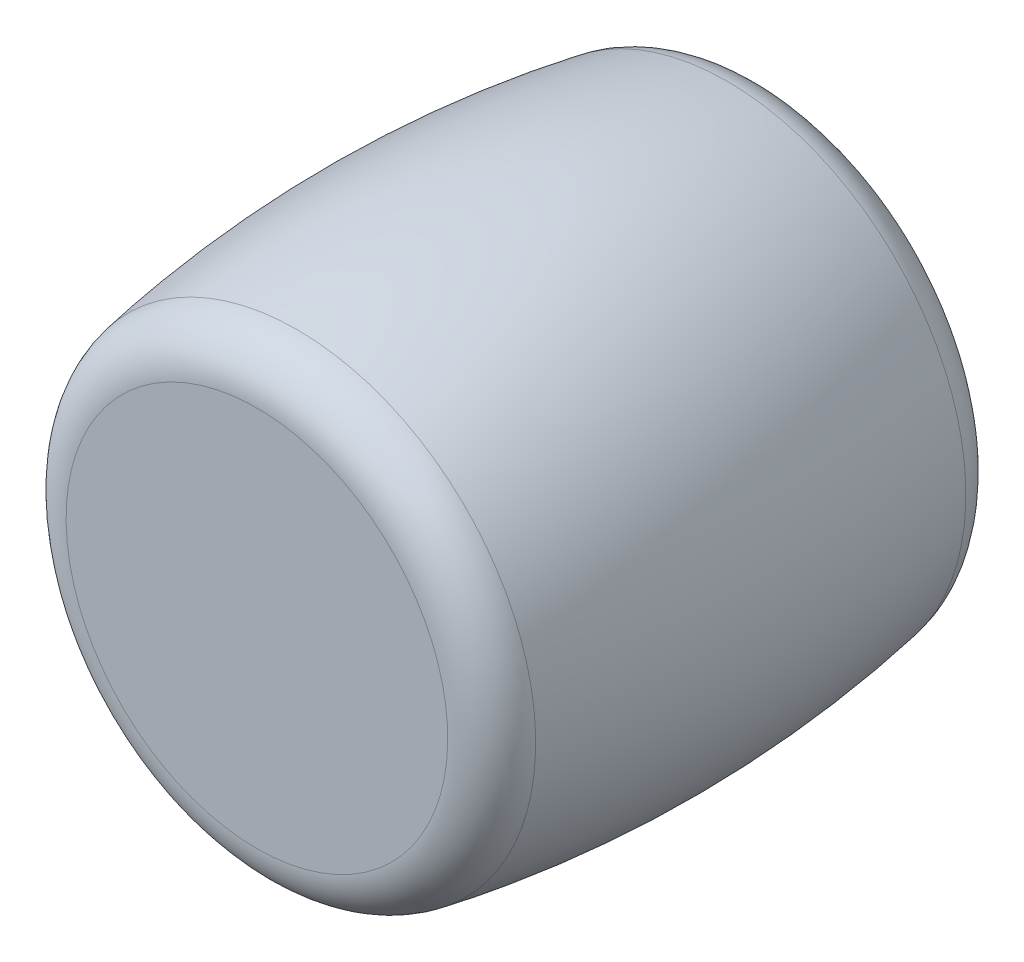
SolidWorks part; units mm, degrees
ref_plane "Front Plane" through (0, 0, 0) normal (0, 0, 1) x (1, 0, 0)
ref_plane "Top Plane" through (0, 0, 0) normal (0, 1, 0) x (1, 0, 0)
ref_plane "Right Plane" through (0, 0, 0) normal (1, 0, 0) x (0, 0, -1)
sketch "Sketch4" plane through (0, 0, 0) normal (1, 0, 0) x (0, 0, -1)
  line L0 (14.7257, -4.75) -> (-17.2963, -4.75) construction
  line L1 (-10.5, 4.75) -> (10.5, 4.75)
  line L2 (-10.5, 4.75) -> (-10.5, -4.75)
  line L3 (-10.5, -4.75) -> (10.5, -4.75)
  line L4 (10.5, 4.75) -> (10.5, -4.75)
  line L5 (-10.5, 4.75) -> (10.5, -4.75) construction
  line L6 (-10.5, -4.75) -> (10.5, 4.75) construction
  arc A0 (-10.5, 4.75) -> (10.5, 4.75) centre (0, -44.6464) cw
  point P0 (0, 0)
  dimension "D1" = 9.5
  dimension "D2" = 21
revolve "Revolve1" add sketch "Sketch4" angle 360 about L0
fillet "Fillet1" radius 2 2 edges at (0, 4.75, -10.5) (0, 4.75, 10.5)
scale "Scale1" scale about origin uniform scaling yes scale factor 0.5
